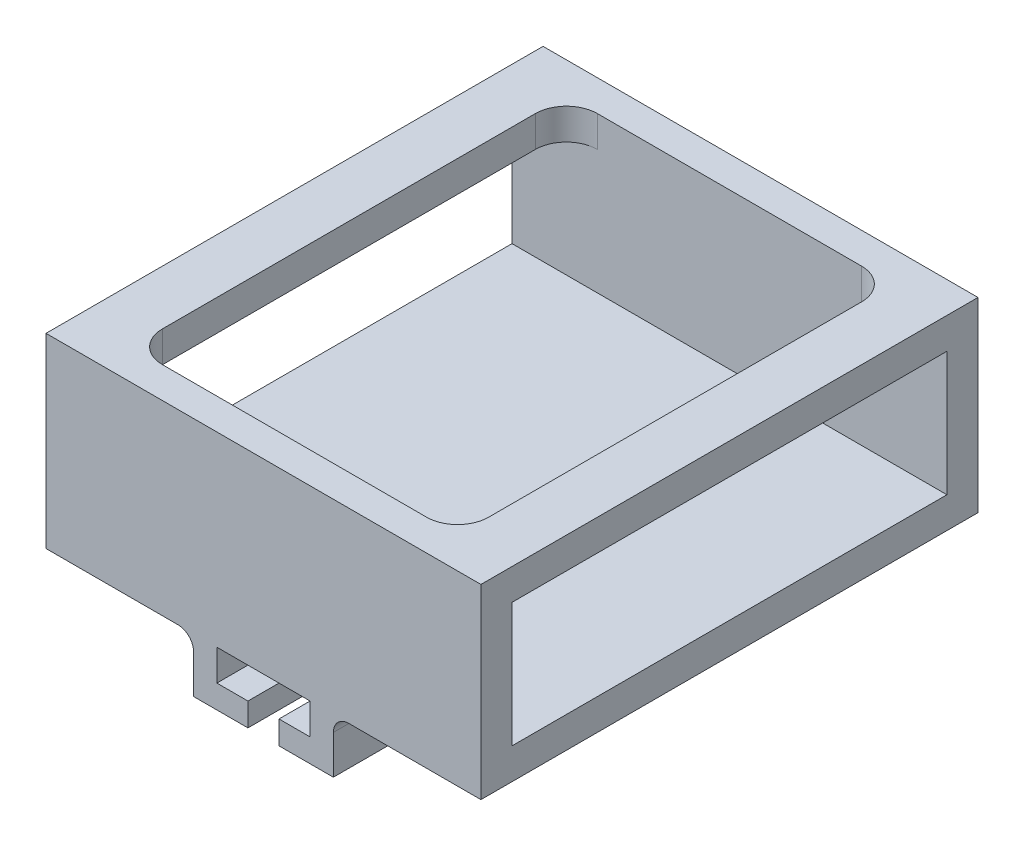
SolidWorks part; units mm, degrees
ref_plane "前视基准面" through (0, 0, 0) normal (0, 0, 1) x (1, 0, 0)
ref_plane "上视基准面" through (0, 0, 0) normal (0, 1, 0) x (1, 0, 0)
ref_plane "右视基准面" through (0, 0, 0) normal (1, 0, 0) x (0, 0, -1)
sketch "草图1" plane through (0, 0, 0) normal (0, 0, 1) x (1, 0, 0)
  line L0 (0, 6) -> (0, -9.5) construction
  line L1 (-14, 6) -> (14, 6)
  line L2 (-14, 6) -> (-14, -6)
  line L3 (-14, -6) -> (14, -6)
  line L4 (14, 6) -> (14, -6)
  line L5 (-14, 6) -> (14, -6) construction
  line L6 (-14, -6) -> (14, 6) construction
  line L7 (4.5, -9.5) -> (-4.5, -9.5)
  line L8 (4.5, -9.5) -> (4.5, -6)
  line L9 (4.5, -6) -> (-4.5, -6)
  line L10 (-4.5, -9.5) -> (-4.5, -6)
  line L11 (4.5, -9.5) -> (-4.5, -6) construction
  line L12 (4.5, -6) -> (-4.5, -9.5) construction
  point P0 (0, 0)
  point P6 (0, -7.75)
  dimension "D1" = 28
  dimension "D2" = 12
  dimension "D3" = 9.5
  dimension "D4" = 3.5
extrude "凸台-拉伸1" add sketch "草图1" along normal blind 32 contours L4 L1 L2 L3 | L10 L7 L8 L3
sketch "草图2" plane through (0, 0, 0) normal (0, 0, -1) x (-1, 0, 0)
  line L0 (-3, -6) -> (3, -6)
  line L1 (3, -6) -> (3, -8)
  line L2 (3, -8) -> (-3, -8)
  line L3 (-3, -8) -> (-3, -6)
  line L4 (0, 6) -> (0, -9.5) construction
  line L5 (14, 6) -> (-14, 6) construction
  line L6 (-4.5, -9.5) -> (4.5, -9.5) construction
  line L7 (-1, -8) -> (-1, -9.5)
  line L8 (-1, -9.5) -> (1, -9.5)
  line L9 (1, -9.5) -> (1, -8)
  point P11 (0, -6)
  line M9 (-4.5, -9.5) -> (4.5, -9.5)
  dimension "D1" = 2
  dimension "D2" = 6
  dimension "D3" = 2
extrude "切除-拉伸1" cut sketch "草图2" against normal through all contours L4 L0 L3 L2 | L0 L4 L2 L1 | L4 L2 L7 M9 | L2 L4 L8 L9
sketch "草图3" plane through (-4.5, 0, 0) normal (-1, 0, 0) x (0, 0, 1)
  line L0 (8, -9.5) -> (8, -8.5)
  line L1 (32, -9.5) -> (0, -9.5) construction
  line L2 (8, -8.5) -> (10, -8.5)
  line L3 (10, -8.5) -> (10, -9.5)
  line L4 (0, -9.5) -> (0, -6) construction
  line L5 (16, -6) -> (16, -9.5) construction
  line L6 (32, -6) -> (0, -6) construction
  line L7 (8, -9.5) -> (10, -9.5)
  line L8 (22, -8.5) -> (22, -9.5)
  line L9 (24, -9.5) -> (24, -8.5)
  line L10 (24, -8.5) -> (22, -8.5)
  line L11 (24, -9.5) -> (22, -9.5)
  dimension "D1" = 1
  dimension "D2" = 8
  dimension "D3" = 2
extrude "切除-拉伸2" cut sketch "草图3" against normal through all
fillet "圆角1" radius 1 2 edges at (-4.5, -6, 16) (4.5, -6, 16)
sketch "草图6" plane through (14, 0, 0) normal (1, 0, 0) x (0, 0, -1)
  line L0 (-16, 6) -> (-16, -6) construction
  line L1 (-32, 6) -> (0, 6) construction
  line L2 (-32, -6) -> (0, -6) construction
  line L3 (-32, 0) -> (0, 0) construction
  line L4 (-32, 6) -> (-32, -6) construction
  line L6 (-30, 4) -> (-2, 4)
  line L7 (-30, 4) -> (-30, -4)
  line L8 (-30, -4) -> (-2, -4)
  line L9 (-2, 4) -> (-2, -4)
  line L10 (-30, 4) -> (-2, -4) construction
  line L11 (-30, -4) -> (-2, 4) construction
  point P11 (-16, 0)
  dimension "D1" = 2
  dimension "D2" = 2
extrude "切除-拉伸5" cut sketch "草图6" against normal through all
sketch "草图5" plane through (0, 6, 0) normal (0, 1, 0) x (1, 0, 0)
  line L0 (-14, -32) -> (14, -32) construction
  line L1 (10.5, -2) -> (-10.5, -2)
  line L2 (10.5, -2) -> (10.5, -30)
  line L3 (10.5, -30) -> (-10.5, -30)
  line L4 (-10.5, -2) -> (-10.5, -30)
  line L5 (10.5, -2) -> (-10.5, -30) construction
  line L6 (10.5, -30) -> (-10.5, -2) construction
  line L7 (-14, 0) -> (14, 0) construction
  line L8 (14, -32) -> (14, 0) construction
  line L9 (-14, -32) -> (-14, 0) construction
  point P0 (0, -16)
  dimension "D1" = 2
  dimension "D2" = 2
  dimension "D3" = 3.5
  dimension "D4" = 3.5
extrude "切除-拉伸4" cut sketch "草图5" against normal up to next
fillet "圆角2" radius 2 4 edges at (10.5, 5, 2) (-10.5, 5, 2) (10.5, 5, 30) (-10.5, 5, 30)
